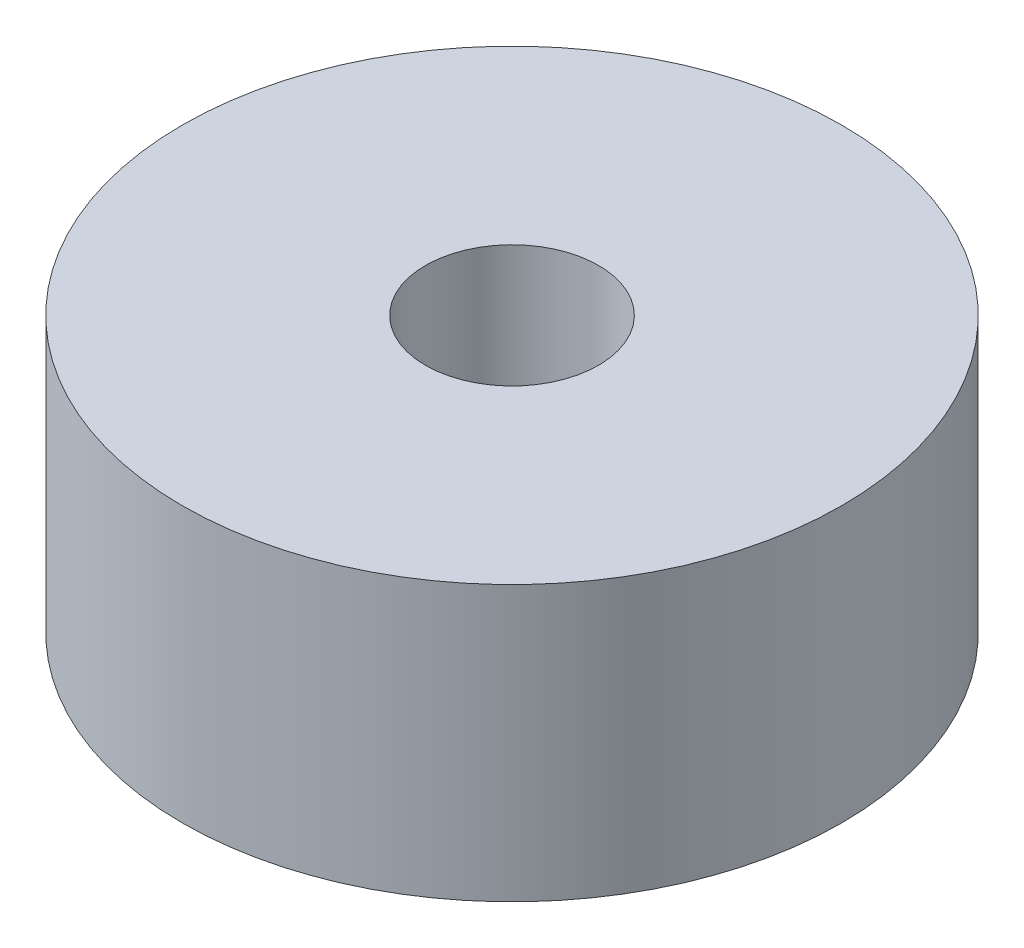
SolidWorks part; units mm, degrees
ref_plane "Front Plane" through (0, 0, 0) normal (0, 0, 1) x (1, 0, 0)
ref_plane "Top Plane" through (0, 0, 0) normal (0, 1, 0) x (1, 0, 0)
ref_plane "Right Plane" through (0, 0, 0) normal (1, 0, 0) x (0, 0, -1)
sketch "Sketch1" plane through (0, 0, 0) normal (0, 1, 0) x (1, 0, 0)
  circle A1 centre (0, 0) radius 3.81
  dimension "D1" = 7.62
extrude "Boss-Extrude1" add sketch "Sketch1" along normal blind 3.175
sketch "Sketch2" plane through (0, 3.175, 0) normal (0, 1, 0) x (1, 0, 0)
  circle A0 centre (0, 0) radius 1
  dimension "D1" = 2
extrude "Cut-Extrude1" cut sketch "Sketch2" against normal blind 3.175
